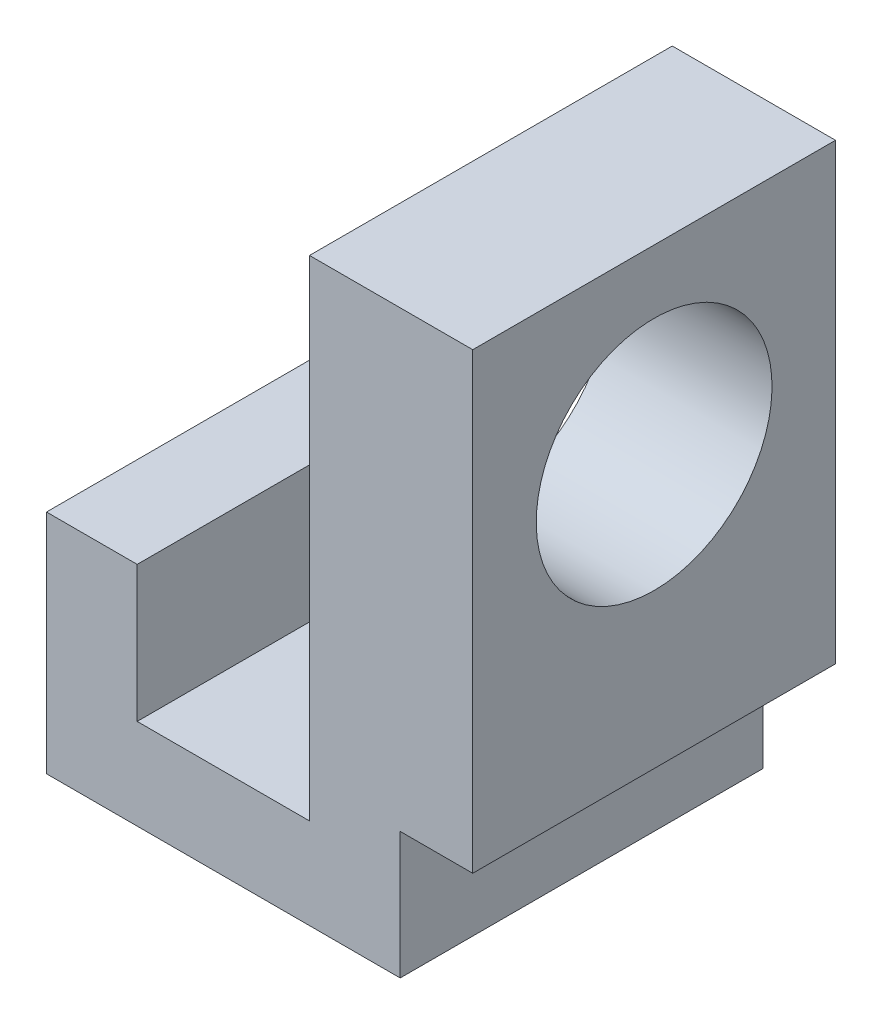
SolidWorks part; units mm, degrees
ref_plane "Front Plane" through (0, 0, 0) normal (0, 0, 1) x (1, 0, 0)
ref_plane "Top Plane" through (0, 0, 0) normal (0, 1, 0) x (1, 0, 0)
ref_plane "Right Plane" through (0, 0, 0) normal (1, 0, 0) x (0, 0, -1)
sketch "Sketch1" plane through (0, 0, 0) normal (0, 0, 1) x (1, 0, 0)
  line L0 (0, 0) -> (39, 0)
  line L1 (39, 0) -> (39, 14)
  line L2 (39, 14) -> (47, 14)
  line L3 (47, 14) -> (47, 64)
  line L4 (47, 64) -> (29, 64)
  line L5 (29, 64) -> (29, 10)
  line L6 (29, 10) -> (10, 10)
  line L7 (10, 10) -> (10, 25)
  line L8 (10, 25) -> (0, 25)
  line L9 (0, 25) -> (0, 0)
  point P3 (39, 7)
  dimension "D1" = 47
  dimension "D2" = 29
  dimension "D3" = 10
  dimension "D4" = 25
  dimension "D5" = 64
  dimension "D6" = 18
  dimension "D7" = 14
  dimension "D8" = 10
extrude "Boss-Extrude1" add sketch "Sketch1" against normal blind 40
sketch "Sketch2" plane through (29, 0, 0) normal (-1, 0, 0) x (0, 0, 1)
  line L0 (-40, 10) -> (0, 10) construction
  line L3 (-20, 44) -> (-20, 10) construction
  circle A0 centre (-20, 44) radius 13
  dimension "D1" = 34
  dimension "D2" = 26
extrude "Cut-Extrude1" cut sketch "Sketch2" against normal blind 18
